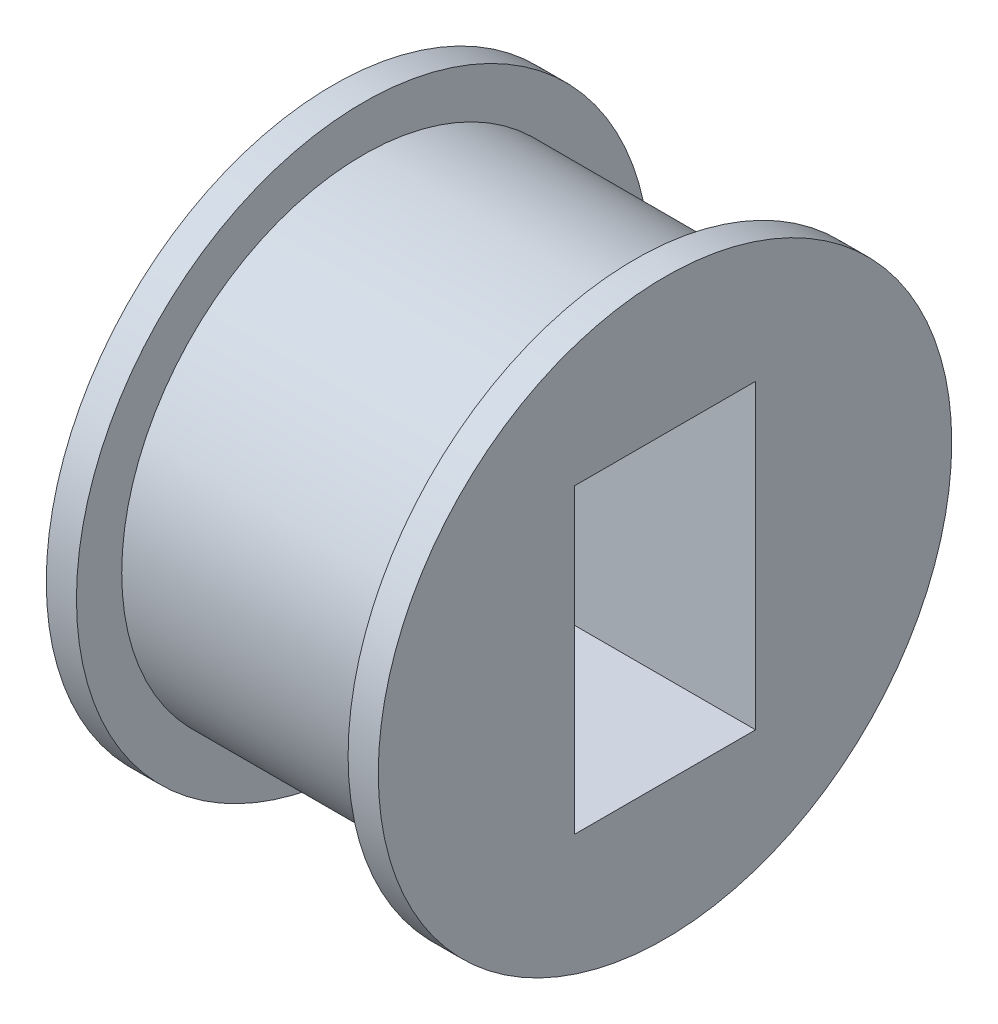
SolidWorks part; units mm, degrees
ref_plane "Front Plane" through (0, 0, 0) normal (0, 0, 1) x (1, 0, 0)
ref_plane "Top Plane" through (0, 0, 0) normal (0, 1, 0) x (1, 0, 0)
ref_plane "Right Plane" through (0, 0, 0) normal (1, 0, 0) x (0, 0, -1)
sketch "Sketch2" plane through (0, 0, 0) normal (1, 0, 0) x (0, 0, -1)
  circle A0 centre (0, 0) radius 40
  dimension "D1" = 80
extrude "Boss-Extrude1" add sketch "Sketch2" along normal mid plane 50
ref_plane "Plane1" through (25, 0, 0) normal (1, 0, 0) x (0, 0, -1)
sketch "Sketch3" plane through (25, 0, 0) normal (1, 0, 0) x (0, 0, -1)
  circle A0 centre (0, 0) radius 47.5
  dimension "D1" = 95
extrude "Boss-Extrude2" add sketch "Sketch3" along normal mid plane 5
mirror "Mirror1" about plane through (0, 0, 0) normal (1, 0, 0) of "Boss-Extrude2"
sketch "Sketch4" plane through (25, 0, 0) normal (1, 0, 0) x (0, 0, -1)
  line L1 (-15, 25) -> (15, 25)
  line L2 (-15, 25) -> (-15, -25)
  line L3 (-15, -25) -> (15, -25)
  line L4 (15, 25) -> (15, -25)
  line L5 (-15, 25) -> (15, -25) construction
  line L6 (-15, -25) -> (15, 25) construction
  point P0 (0, 0)
  dimension "D1" = 50
  dimension "D2" = 30
extrude "Cut-Extrude1" cut sketch "Sketch4" against normal through all both and the other way through all
